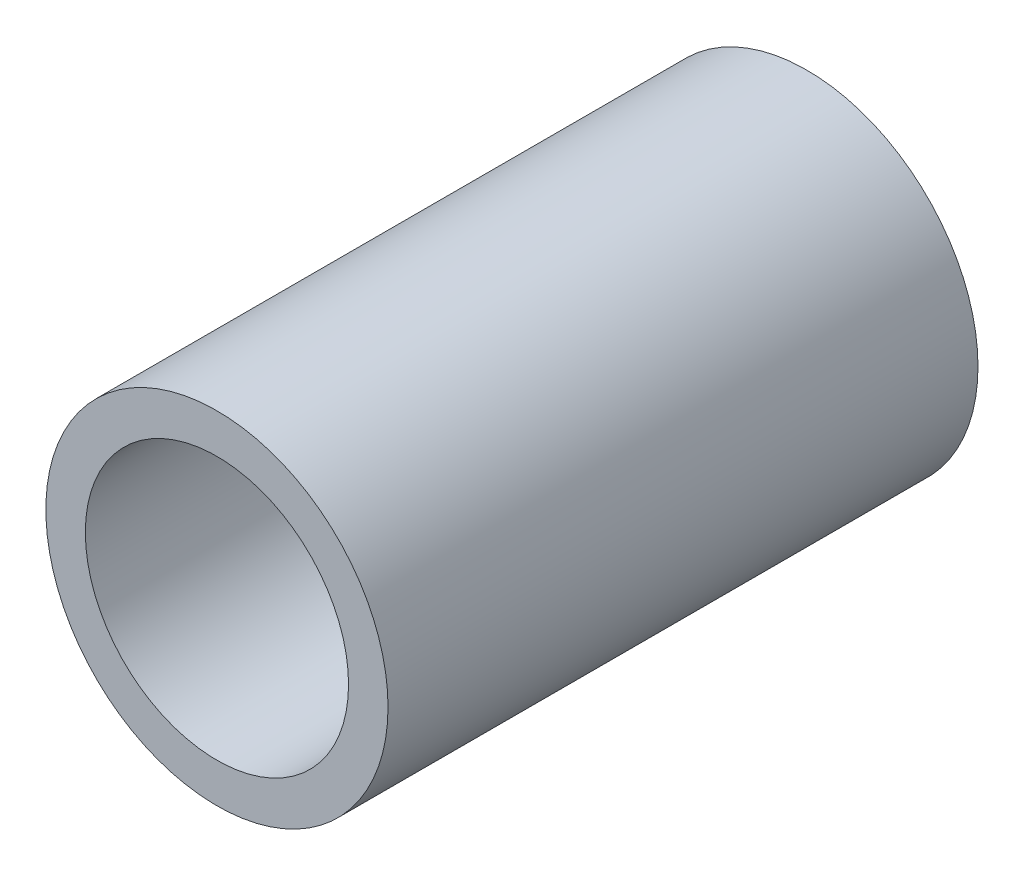
SolidWorks part; units mm, degrees
ref_plane "Front Plane" through (0, 0, 0) normal (0, 0, 1) x (1, 0, 0)
ref_plane "Top Plane" through (0, 0, 0) normal (0, 1, 0) x (1, 0, 0)
ref_plane "Right Plane" through (0, 0, 0) normal (1, 0, 0) x (0, 0, -1)
sketch "Sketch1" plane through (0, 0, 0) normal (0, 0, 1) x (1, 0, 0)
  circle A0 centre (0, 0) radius 3.25
  circle A1 centre (0, 0) radius 2.5
  dimension "D1" = 6.5
  dimension "D2" = 5
extrude "Boss-Extrude1" add sketch "Sketch1" along normal blind 11.207
